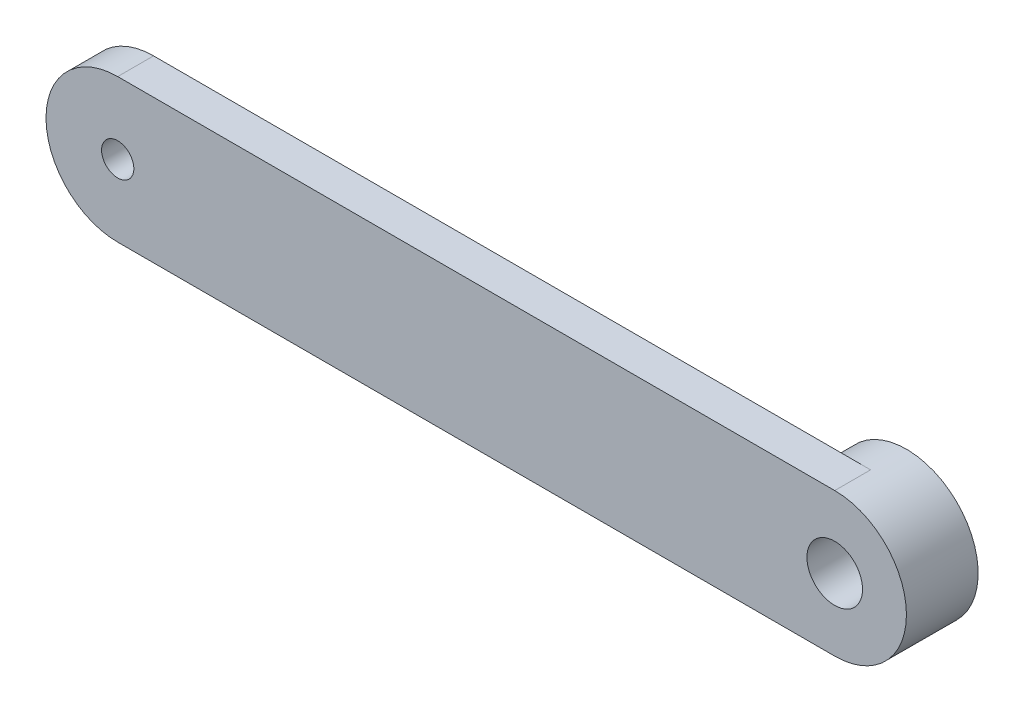
SolidWorks part; units mm, degrees
ref_plane "前视基准面" through (0, 0, 0) normal (0, 0, 1) x (1, 0, 0)
ref_plane "上视基准面" through (0, 0, 0) normal (0, 1, 0) x (1, 0, 0)
ref_plane "右视基准面" through (0, 0, 0) normal (1, 0, 0) x (0, 0, -1)
other "Configuration Table"
sketch "草图1" plane through (0, 0, 0) normal (0, 0, 1) x (1, 0, 0)
  line L0 (20, 0) -> (-20, 0) construction
  line L1 (20, -4) -> (-20, -4)
  line L2 (20, 4) -> (-20, 4)
  arc A0 (20, -4) -> (20, 4) centre (20, 0) ccw
  arc A1 (-20, 4) -> (-20, -4) centre (-20, 0) ccw
  circle A2 centre (20, 0) radius 1.55
  circle A3 centre (-20, 0) radius 0.9
  point P3 (0, 0)
  dimension "D2" = 4
  dimension "D3" = 3.1
  dimension "D4" = 1.8
  dimension "D1" = 40
extrude "凸台-拉伸1" add sketch "草图1" along normal blind 2
sketch "草图2" plane through (0, 0, 0) normal (0, 0, -1) x (-1, 0, 0)
  circle A0 centre (20, 0) radius 2
  circle A1 centre (20, 0) radius 0.9 construction
  circle A2 centre (20, 0) radius 0.9
  dimension "D1" = 4
extrude "凸台-拉伸2" add sketch "草图2" along normal blind 2
sketch "草图3" plane through (0, 0, 0) normal (0, 0, -1) x (-1, 0, 0)
  circle A0 centre (-20, 0) radius 4
  circle A1 centre (-20, 0) radius 1.55 construction
  circle A2 centre (-20, 0) radius 1.55
  dimension "D1" = 8
extrude "凸台-拉伸3" add sketch "草图3" along normal blind 2
